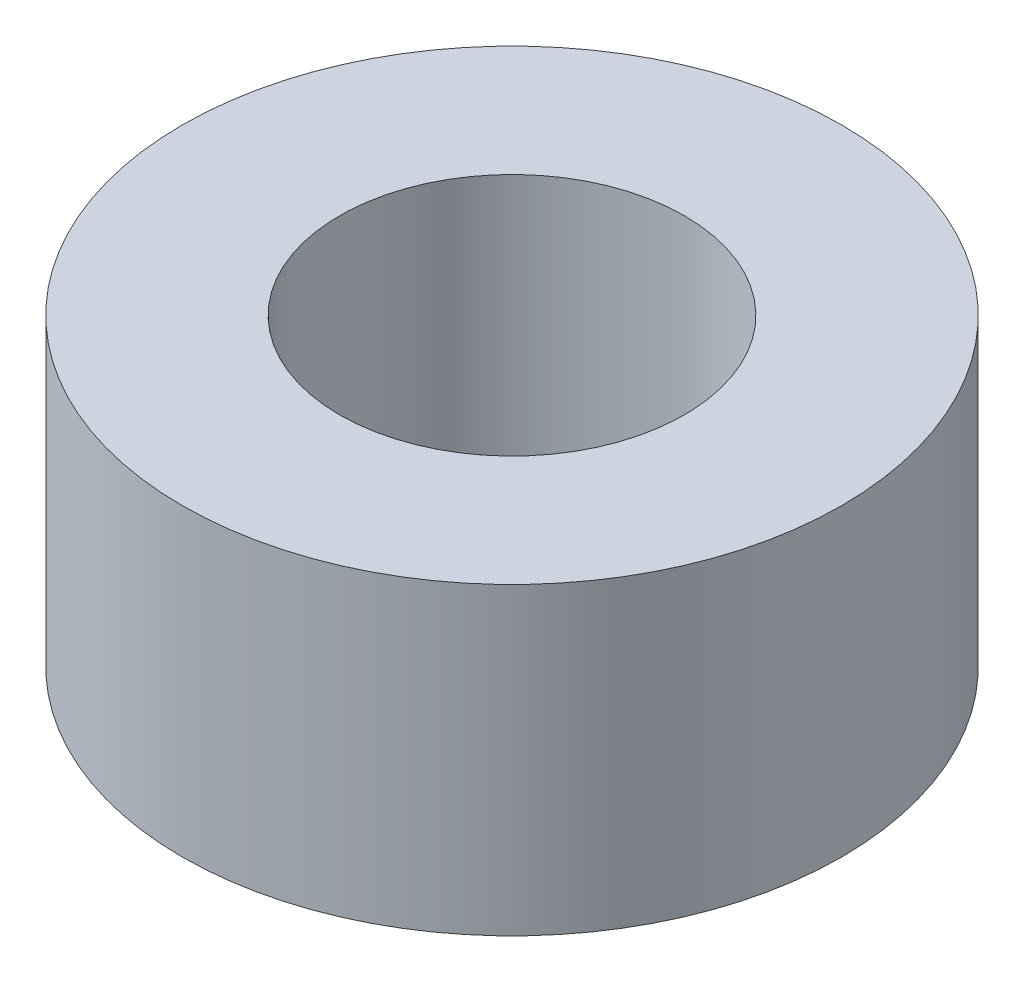
SolidWorks part; units mm, degrees
ref_plane "Front Plane" through (0, 0, 0) normal (0, 0, 1) x (1, 0, 0)
ref_plane "Top Plane" through (0, 0, 0) normal (0, 1, 0) x (1, 0, 0)
ref_plane "Right Plane" through (0, 0, 0) normal (1, 0, 0) x (0, 0, -1)
sketch "Sketch1" plane through (0, 0, 0) normal (0, 1, 0) x (1, 0, 0)
  circle A0 centre (0, 0) radius 3.25
  circle A1 centre (0, 0) radius 1.7
  dimension "D1" = 6.5
  dimension "D2" = 3.4
extrude "Boss-Extrude1" add sketch "Sketch1" along normal blind 3
